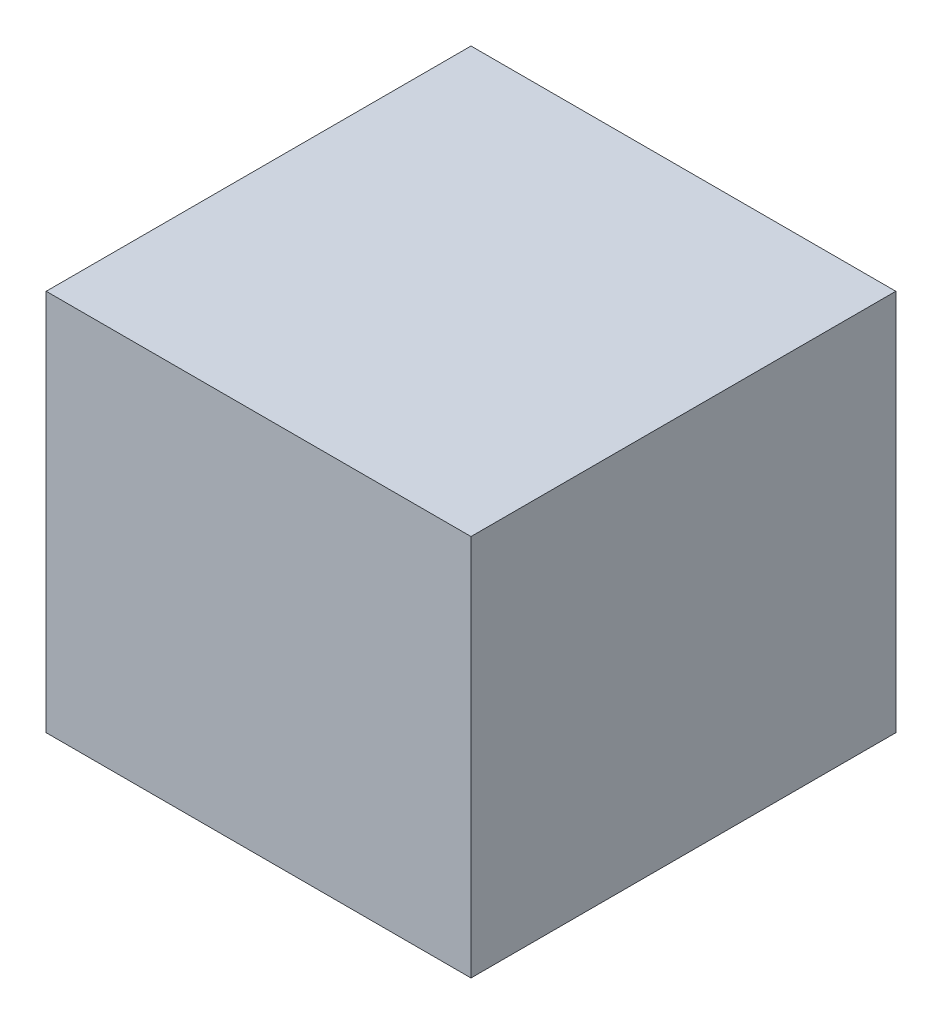
SolidWorks part; units mm, degrees
material "AISI 4130 Steel, normalized at 870C"
ref_plane "Front Plane" through (0, 0, 0) normal (0, 0, 1) x (1, 0, 0)
ref_plane "Top Plane" through (0, 0, 0) normal (0, 1, 0) x (1, 0, 0)
ref_plane "Right Plane" through (0, 0, 0) normal (1, 0, 0) x (0, 0, -1)
sketch "Sketch1" plane through (0, 0, 0) normal (0, 1, 0) x (1, 0, 0)
  line L1 (-2.5, 2.5) -> (2.5, 2.5)
  line L2 (-2.5, 2.5) -> (-2.5, -2.5)
  line L3 (-2.5, -2.5) -> (2.5, -2.5)
  line L4 (2.5, 2.5) -> (2.5, -2.5)
  line L5 (-2.5, 2.5) -> (2.5, -2.5) construction
  line L6 (-2.5, -2.5) -> (2.5, 2.5) construction
  point P0 (0, 0)
  dimension "D1" = 5
  dimension "D2" = 5
extrude "Boss-Extrude1" add sketch "Sketch1" along normal blind 4.5
